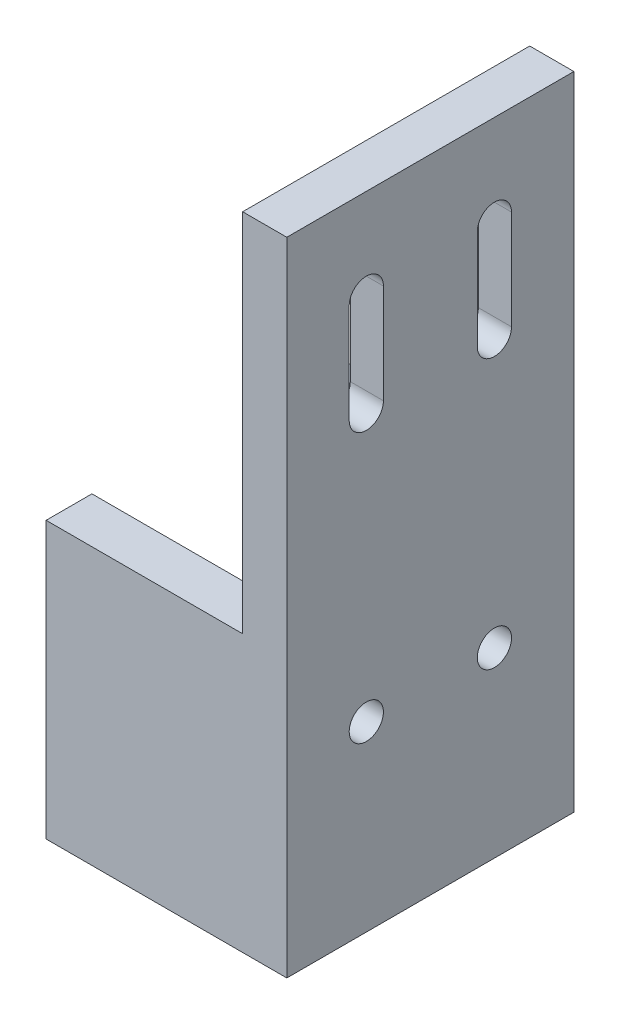
SolidWorks part; units mm, degrees
ref_plane "Front Plane" through (0, 0, 0) normal (0, 0, 1) x (1, 0, 0)
ref_plane "Top Plane" through (0, 0, 0) normal (0, 1, 0) x (1, 0, 0)
ref_plane "Right Plane" through (0, 0, 0) normal (1, 0, 0) x (0, 0, -1)
sketch "ProfileSketch1" plane through (0, 0, 0) normal (0, 0, 1) x (1, 0, 0)
  line L0 (0, 0) -> (4, 0)
  line L1 (4, 0) -> (4, 58.1)
  line L2 (4, 58.1) -> (0, 58.1)
  line L3 (0, 58.1) -> (0, 0)
  dimension "D1" = 58.1
  dimension "D4" = 4
extrude "Boss-Extrude1" add sketch "ProfileSketch1" along normal blind 26
sketch "ProbeSlidingMountSketch4" plane through (0, 0, 0) normal (-1, 0, 0) x (0, 0, 1)
  line L0 (26, 58.1) -> (0, 58.1) construction
  line L3 (5.65, 49.9) -> (5.65, 40.9)
  line L4 (8.75, 49.9) -> (8.75, 40.9)
  line L5 (17.25, 49.9) -> (17.25, 40.9)
  line L6 (20.35, 49.9) -> (20.35, 40.9)
  line L7 (0, 58.1) -> (0, 0) construction
  line L8 (26, 0) -> (0, 0) construction
  line L9 (26, 58.1) -> (26, 0) construction
  arc A0 (8.75, 49.9) -> (5.65, 49.9) centre (7.2, 49.9) ccw
  arc A1 (5.65, 40.9) -> (8.75, 40.9) centre (7.2, 40.9) ccw
  arc A2 (20.35, 49.9) -> (17.25, 49.9) centre (18.8, 49.9) ccw
  arc A3 (17.25, 40.9) -> (20.35, 40.9) centre (18.8, 40.9) ccw
  circle A4 centre (7.2, 16.5) radius 1.55
  circle A5 centre (18.8, 16.5) radius 1.55
  dimension "D1" = 3.1
  dimension "D6" = 3.1
  dimension "D2" = 9
  dimension "D7" = 24.4
  dimension "D3" = 17.2
  dimension "D8" = 40.9
  dimension "D4" = 11.6
  dimension "D5" = 7.2
  dimension "D9" = 7.2
extrude "ProbeSlidingMountCut-Extrude3" cut sketch "ProbeSlidingMountSketch4" against normal through all
sketch "ProbeSlidingMountChannelSketch5" plane through (0, 0, 0) normal (-1, 0, 0) x (0, 0, 1)
  line L0 (7.2, 49.9) -> (7.2, 40.9) construction
  line L1 (10.4, 49.9) -> (10.4, 40.9)
  line L2 (4, 49.9) -> (4, 40.9)
  line L3 (18.8, 49.9) -> (18.8, 40.9) construction
  line L4 (22, 49.9) -> (22, 40.9)
  line L5 (15.6, 49.9) -> (15.6, 40.9)
  arc A0 (10.4, 49.9) -> (4, 49.9) centre (7.2, 49.9) ccw
  arc A1 (4, 40.9) -> (10.4, 40.9) centre (7.2, 40.9) ccw
  arc A2 (22, 49.9) -> (15.6, 49.9) centre (18.8, 49.9) ccw
  arc A3 (15.6, 40.9) -> (22, 40.9) centre (18.8, 40.9) ccw
  point P4 (7.2, 45.4)
  point P9 (18.8, 45.4)
  dimension "D1" = 6.4
extrude "ProbeSlidingMountChanelCut-Extrude4" cut sketch "ProbeSlidingMountChannelSketch5" against normal blind 1
sketch "InductiveProbeHolderSketch1" plane through (0, 0, 0) normal (-1, 0, 0) x (0, 0, 1)
  line L1 (0, 0) -> (4.15, 0)
  line L2 (0, 0) -> (0, 25)
  line L3 (0, 25) -> (4.15, 25)
  line L4 (4.15, 0) -> (4.15, 25)
  line L5 (26, 0) -> (21.85, 0)
  line L6 (26, 0) -> (26, 25)
  line L7 (26, 25) -> (21.85, 25)
  line L8 (21.85, 0) -> (21.85, 25)
  dimension "D1" = 17.7
  dimension "D2" = 25
extrude "InductiveProbeHolderBoss-Extrude2" add sketch "InductiveProbeHolderSketch1" along normal blind 17.8
equation "\"ProbeMountHeight\"= \"ProbeMountDepth\" + \"ProbeMountUpperHeight\""
equation "\"D1@ProfileSketch1\"=\"ProbeMountHeight\" + 30mm"
equation "\"D1@Boss-Extrude1\"= \"ProbeBodyWidth\""
equation "\"ProbeBodyWidth\"= 26mm"
equation "\"ProbeMountUpperHeight\"= \"M3ScrewButtonHeadHeight\" * 2 + \"M3ScrewDiameter\" * 5 + \"M3ScrewButtonHeadHeight\" * 2"
equation "\"D4@ProfileSketch1\"=\"ProbeMountDepth\"+1mm"
equation "\"M3ScrewButtonHeadHeight\"= 2.4mm"
equation "\"D1@ProbeSlidingMountSketch4\" = \"M3ScrewDiameter\""
equation "\"D2@ProbeSlidingMountSketch4\" = 3mm * 3"
equation "\"M3ScrewDiameter\"= 3.1mm"
equation "\"ProbeMountDepth\"= 3mm"
equation "\"M3ScrewButtonHeadDiameter\"= 5.9mm"
equation "\"D1@ProbeSlidingMountChannelSketch5\"=\"M3ScrewButtonHeadDiameter\"+ .5mm"
equation "\"D7@ProbeSlidingMountSketch4\"=13.5+10.9"
equation "\"InductiveProbeWidth\"= 17.7mm"
equation "\"D1@InductiveProbeHolderSketch1\" = \"InductiveProbeWidth\""
equation "\"ProbeMountingHoleDistance\"=11.6"
equation "\"D5@ProbeSlidingMountSketch4\"=(\"ProbeBodyWidth\" - \"ProbeMountingHoleDistance\")/2"
